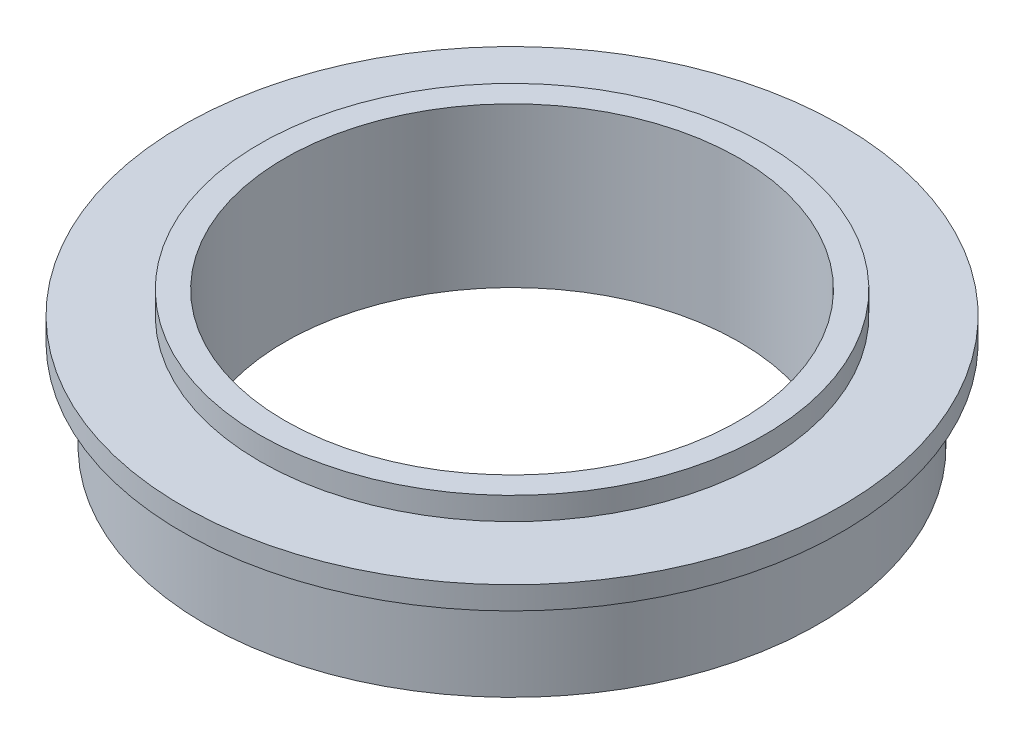
SolidWorks part; units mm, degrees
material "合金钢"
ref_plane "前视基准面" through (0, 0, 0) normal (0, 0, 1) x (1, 0, 0)
ref_plane "上视基准面" through (0, 0, 0) normal (0, 1, 0) x (1, 0, 0)
ref_plane "右视基准面" through (0, 0, 0) normal (1, 0, 0) x (0, 0, -1)
sketch "草图1" plane through (0, 0, 0) normal (0, 0, 1) x (1, 0, 0)
  line L0 (0, 0) -> (0, 4.1687) construction
  line L1 (11.1, 0) -> (13.5, 0)
  line L2 (13.5, 0) -> (13.5, 4)
  line L3 (13.5, 4) -> (14.5, 4)
  line L4 (14.5, 4) -> (14.5, 5)
  line L5 (14.5, 5) -> (11.1, 5)
  line L6 (10, 6) -> (10, -1)
  line L7 (11.1, 5) -> (11.1, 6)
  line L8 (11.1, 6) -> (10, 6)
  line L9 (11.1, 0) -> (11.1, -1)
  line L10 (11.1, -1) -> (10, -1)
  point P3 (10, 4.7327)
  point P8 (10, -1.0519)
  point P15 (10, 5.4402)
  point P16 (10, -0.7814)
  dimension "D1" = 20
  dimension "D2" = 27
  dimension "D3" = 29
  dimension "D4" = 1
  dimension "D5" = 7
  dimension "D6" = 22.2
  dimension "D7" = 5
  dimension "D8" = 1
revolve "旋转1" add sketch "草图1" angle 360 about L0
